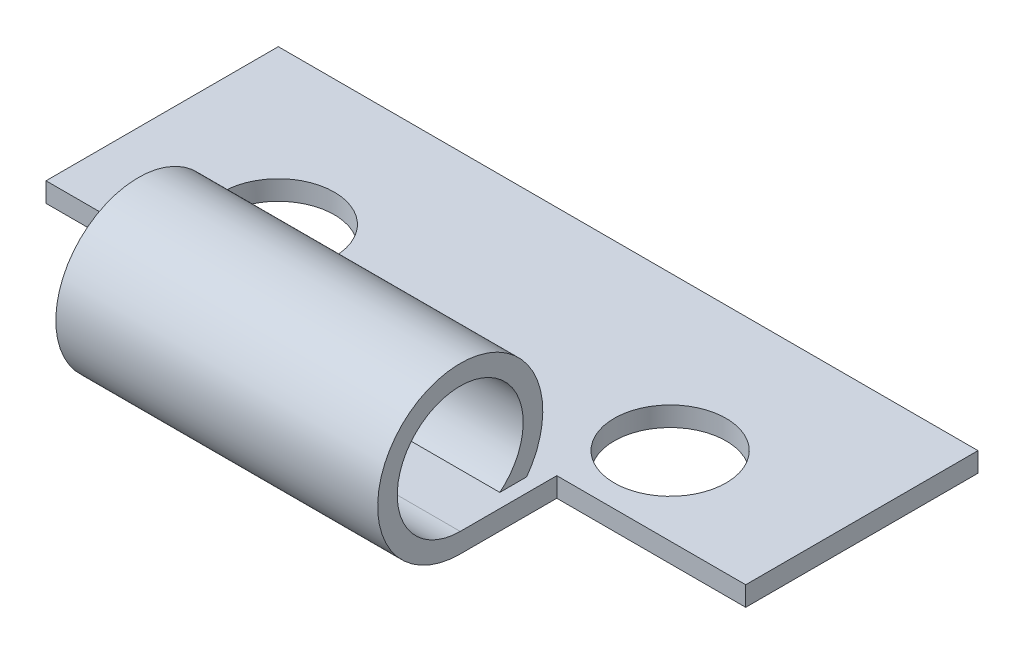
SolidWorks part; units mm, degrees
ref_plane "Alzado" through (0, 0, 0) normal (0, 0, 1) x (1, 0, 0)
ref_plane "Planta" through (0, 0, 0) normal (0, 1, 0) x (1, 0, 0)
ref_plane "Vista lateral" through (0, 0, 0) normal (1, 0, 0) x (0, 0, -1)
sketch "Croquis4" plane through (0, 0, 0) normal (1, 0, 0) x (0, 0, -1)
  line L0 (0, 0) -> (14, 0) construction
  line L1 (14, 0) -> (14, 0.7)
  line L2 (14, 0.7) -> (2.25, 0.7)
  line L3 (4.6249, 1.2) -> (3.6642, 1.2)
  line L4 (2.25, 0) -> (14, 0)
  arc A0 (3.6642, 1.2) -> (2.25, 0.7) centre (2.25, 2.95) ccw
  arc A1 (4.6249, 1.2) -> (2.25, 0) centre (2.25, 2.95) ccw
  circle A2 centre (2.25, 2.95) radius 2.95 construction
  circle A3 centre (2.25, 2.95) radius 2.25 construction
  point P8 (0, 2.95)
  dimension "D1" = 4.5
  dimension "D2" = 14
  dimension "D3" = 0.7
  dimension "D5" = 0.5
  dimension "D4" = 0.7
extrude "Saliente-Extruir1" add sketch "Croquis4" along normal mid plane 25
sketch "Croquis5" plane through (0, 0.7, 0) normal (0, 1, 0) x (1, 0, 0)
  line L0 (12.5, 14) -> (12.5, 2.25) construction
  line L1 (12.5, 14) -> (-12.5, 14) construction
  line L2 (0, 14) -> (0, 6.4236) construction
  circle A0 centre (7, 8.5) radius 2
  circle A1 centre (-7, 8.5) radius 2
  dimension "D1" = 4
  dimension "D2" = 5.5
  dimension "D3" = 5.5
extrude "Cortar-Extruir1" cut sketch "Croquis5" against normal up to next
sketch "Croquis6" plane through (0, 0.7, 0) normal (0, 1, 0) x (1, 0, 0)
  line L0 (-5.75, 5.7) -> (-13.0486, 5.7)
  line L1 (-5.75, 5.7) -> (5.75, 5.7) construction
  line L2 (-5.75, 5.7) -> (-5.75, -0.7)
  line L3 (-5.75, -0.7) -> (5.75, -0.7)
  line L4 (5.75, 5.7) -> (5.75, -0.7)
  line L5 (-12.5, -0.7) -> (12.5, -0.7) construction
  line L6 (12.5, 5.2) -> (-12.5, 5.2) construction
  line L7 (-13.0486, 5.7) -> (-13.0486, -1.9647)
  line L8 (-13.0486, -1.9647) -> (14.1937, -1.9647)
  line L9 (14.1937, -1.9647) -> (14.1937, 5.7)
  line L10 (14.1937, 5.7) -> (5.75, 5.7)
  point P8 (0, -0.7)
  dimension "D1" = 0.5
  dimension "D2" = 11.5
extrude "Cortar-Extruir2" cut sketch "Croquis6" along normal through all both and the other way through all
